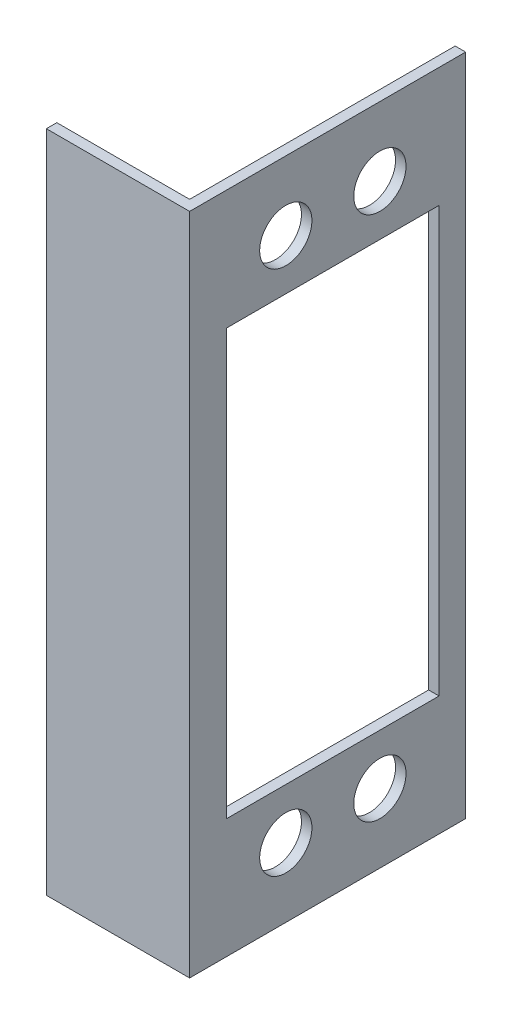
SolidWorks part; units mm, degrees
ref_plane "Front Plane" through (0, 0, 0) normal (0, 0, 1) x (1, 0, 0)
ref_plane "Top Plane" through (0, 0, 0) normal (0, 1, 0) x (1, 0, 0)
ref_plane "Right Plane" through (0, 0, 0) normal (1, 0, 0) x (0, 0, -1)
sketch "Sketch1" plane through (0, 0, 0) normal (0, 1, 0) x (1, 0, 0)
  line L1 (0, 0) -> (13.7, 0)
  line L2 (0, 0) -> (0, 1)
  line L3 (0, 1) -> (13.7, 1)
  line L4 (13.7, 0) -> (13.7, 1)
  line L5 (13.7, 1) -> (12.7, 1)
  line L6 (13.7, 1) -> (13.7, 26.4)
  line L7 (13.7, 26.4) -> (12.7, 26.4)
  line L8 (12.7, 1) -> (12.7, 26.4)
  dimension "D1" = 1
  dimension "D2" = 1
  dimension "D3" = 12.7
  dimension "D4" = 25.4
extrude "Boss-Extrude1" add sketch "Sketch1" along normal blind 63.5 contours L8 L3 L6 L7 | L1 L4 L3 L2
sketch "Sketch2" plane through (12.7, 0, 0) normal (-1, 0, 0) x (0, 0, 1)
  line L0 (-1, 0) -> (-26.4, 0) construction
  line L1 (-23.86, 52.07) -> (-3.54, 52.07)
  line L2 (-23.86, 52.07) -> (-23.86, 11.43)
  line L3 (-23.86, 11.43) -> (-3.54, 11.43)
  line L4 (-3.54, 52.07) -> (-3.54, 11.43)
  line L5 (-26.4, 63.5) -> (-26.4, 0) construction
  point P6 (-13.7, 0)
  point P7 (-13.7, 11.43)
  point P10 (-26.4, 31.75)
  point P11 (-23.86, 31.75)
  dimension "D1" = 20.32
  dimension "D2" = 40.64
extrude "Cut-Extrude1" cut sketch "Sketch2" against normal through all
hole_wizard "Ø5.0mm Dowel Hole1" positions "Sketch3" profile "Sketch4" hole size "Ø5.0" standard "ANSI Metric" end condition through all
sketch "Sketch3" plane through (12.7, 0, 0) normal (-1, 0, 0) x (0, 0, 1)
  point P0 (-9.2, 6.6)
  point P2 (-18.2, 56.9)
  point P4 (-9.2, 56.9)
  point P6 (-18.2, 6.6)
  point P14 (-18.2, 56.9)
  point P16 (-9.2, 56.9)
  point P18 (-9.2, 6.6)
  point P20 (-18.2, 6.6)
sketch "Sketch4" plane through (12.7, 6.6, -9.2) normal (0, 1, 0) x (0, 0, 1)
  line L0 (0, 0) -> (0, 1)
  line L1 (0, 1) -> (2.5, 1)
  line L2 (2.5, 1) -> (2.5, 0)
  line L5 (2.5, 0) -> (0, 0)
  line L11 (0, -6.35) -> (0, 107.95) construction
  dimension "Thru Hole Dia." = 5
  dimension "Thru Hole Depth" = 1
equation "\"servo width\"= 1.5866"
equation "\"servo height\"= 0.7874"
equation "\"press fit\"= 0.3mm"
equation "\"D1@Sketch2\"=\"servo height\"+\"press fit\""
equation "\"D2@Sketch2\"=\"servo width\"+\"press fit\""
